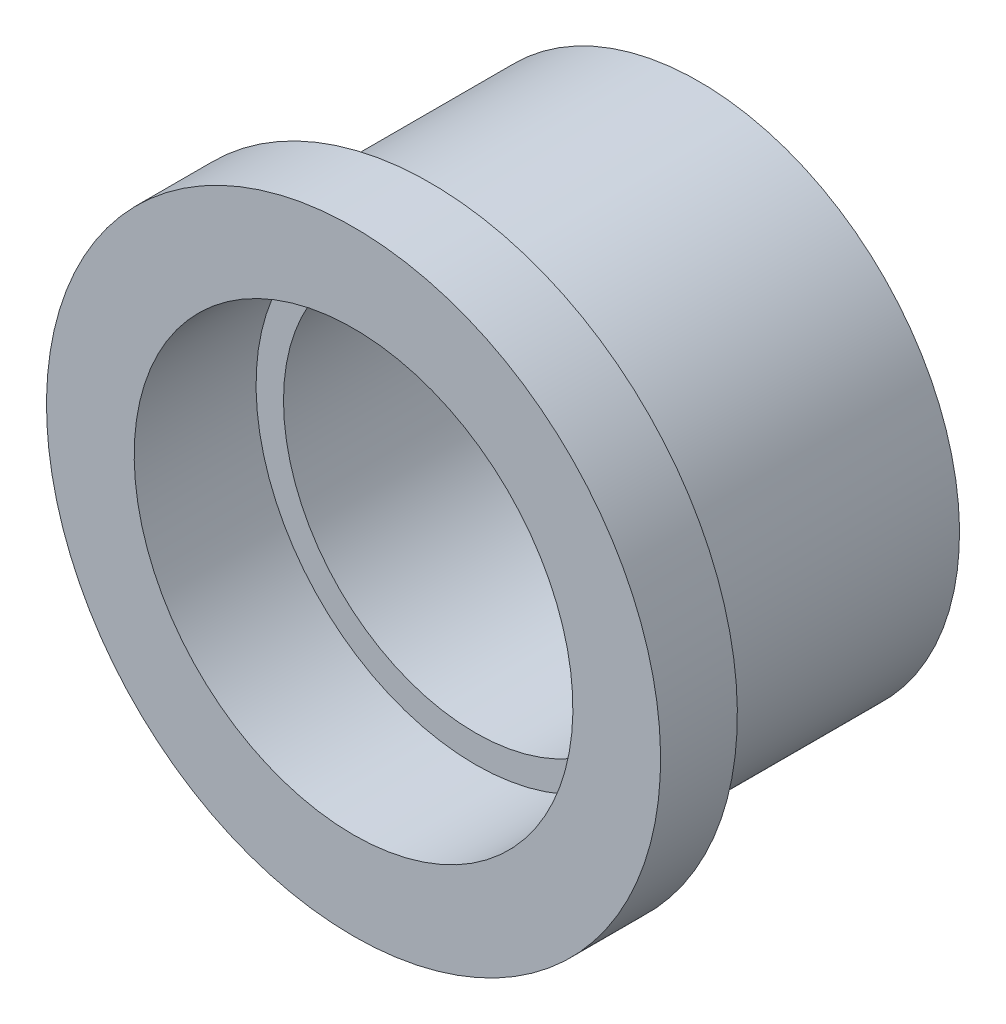
SolidWorks part; units mm, degrees
ref_plane "Plano frontal" through (0, 0, 0) normal (0, 0, 1) x (1, 0, 0)
ref_plane "Plano superior" through (0, 0, 0) normal (0, 1, 0) x (1, 0, 0)
ref_plane "Plano direito" through (0, 0, 0) normal (1, 0, 0) x (0, 0, -1)
sketch "Esboço1" plane through (0, 0, 0) normal (1, 0, 0) x (0, 0, -1)
  line L0 (0, 0) -> (141.7378, 0) construction
  line L2 (45, 25) -> (45, 33.94)
  line L3 (45, 33.94) -> (10, 33.94)
  line L4 (10, 33.94) -> (10, 40)
  line L5 (10, 40) -> (0, 40)
  line L6 (0, 40) -> (0, 28.575)
  line L7 (45, 25) -> (15.875, 25)
  line L8 (15.875, 25) -> (15.875, 28.575)
  line L9 (15.875, 28.575) -> (0, 28.575)
  point P8 (44.5967, 25)
  dimension "D1" = 57.15
  dimension "D2" = 67.88
  dimension "D3" = 10
  dimension "D4" = 80
  dimension "D5" = 50
  dimension "D6" = 15.875
  dimension "D7" = 45
revolve "Revolução1" add sketch "Esboço1" angle 360 about L0
sketch "Esboço2" [suppressed] plane through (0, 0, 0) normal (0, 0, 1) x (1, 0, 0)
  circle A0 centre (0, 0) radius 54.25
  point P3 (0, 54.25)
  point P4 (54.25, 0)
  point P5 (-54.25, 0)
  point P7 (0, -54.25)
  point P8 (0, 0)
  dimension "D1" = 108.5
  dimension "D2" = 4
hole_wizard "Furo roscado de M101" [suppressed] positions "Esboço3" profile "Esboço4" tap size "M10" standard "ISO"
sketch "Esboço3" [suppressed] plane through (0, 0, 0) normal (0, 0, 1) x (1, 0, 0)
  point P0 (-54.25, 0)
  point P3 (0, 54.25)
  point P6 (54.25, 0)
  point P9 (0, -54.25)
sketch "Esboço4" plane through (-54.25, 0, 0) normal (1, 0, 0) x (0, -1, 0)
  line L0 (0, 0) -> (0, 60)
  line L1 (0, 60) -> (4.25, 60)
  line L2 (4.25, 60) -> (4.25, 0)
  line L5 (4.25, 0) -> (0, 0)
  line L11 (0, -6.35) -> (0, 107.95) construction
  dimension "Thru Tap Drill Dia." = 8.5
  dimension "Thru Tap Drill Depth" = 60
cosmetic thread "Rosca de furo1" [suppressed] parameters "D2"=10
cosmetic thread "Rosca de furo2" [suppressed] parameters "D2"=10
cosmetic thread "Rosca de furo3" [suppressed] parameters "D2"=10
cosmetic thread "Rosca de furo4" [suppressed] parameters "D2"=10
ref_plane "Plano1" through (0, 41.75, 0) normal (0, 1, 0) x (1, 0, 0)
hole_wizard "Furo roscado de M10x1.51" [suppressed] positions "Esboço13" profile "Esboço15" tap size "M10x1.5" standard "Ansi Metric"
sketch "Esboço13" plane through (0, 41.75, 0) normal (0, 1, 0) x (1, 0, 0)
  line L0 (26.5, 60) -> (-26.5, 60) construction
  point P0 (0, 35)
  dimension "D1" = 25
sketch "Esboço15" plane through (0, 41.75, -35) normal (1, 0, 0) x (0, 0, 1)
  line L0 (0, 0) -> (0, 68.25)
  line L1 (0, 68.25) -> (4.25, 68.25)
  line L2 (4.25, 68.25) -> (4.25, 0.775)
  line L3 (4.25, 0.775) -> (5.025, 0)
  line L5 (5.025, 0) -> (0, 0)
  line L6 (-4.25, 0.775) -> (-5.025, 0) construction
  line L11 (0, -6.35) -> (0, 107.95) construction
  dimension "Thru Tap Drill Dia." = 8.5
  dimension "Thru Tap Drill Depth" = 68.25
  dimension "Near C'Sink Dia." = 10.05
  dimension "Near C'Sink Angle" = 90
cosmetic thread "Rosca de furo5" [suppressed] parameters "D2"=10
pattern_circular "PadrãoCircular1" [suppressed] count 2 over 360
cosmetic thread "Rosca de furo6" [suppressed] parameters "D2"=10
